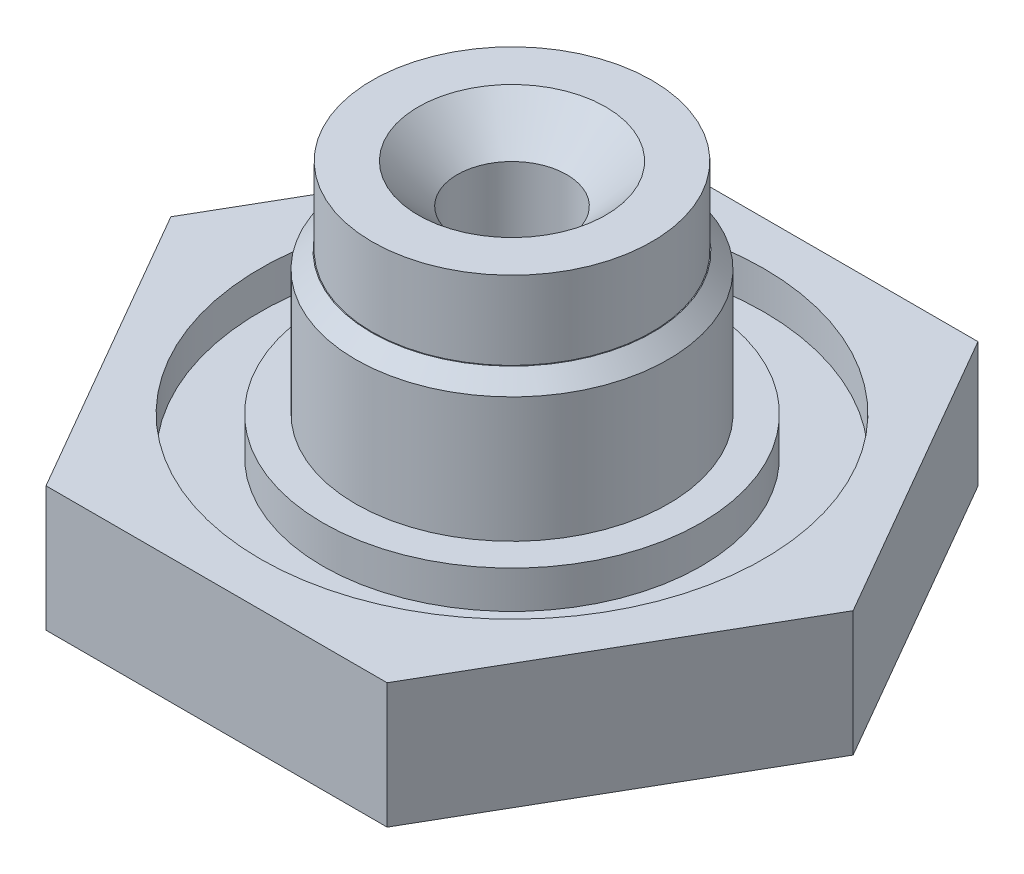
SolidWorks part; units mm, degrees
material "Acier allié inoxydable"
ref_plane "Front" through (0, 0, 0) normal (0, 0, 1) x (1, 0, 0)
ref_plane "Top" through (0, 0, 0) normal (0, 1, 0) x (1, 0, 0)
ref_plane "Right" through (0, 0, 0) normal (1, 0, 0) x (0, 0, -1)
sketch "Esquisse1" plane through (0, 0, 0) normal (0, 0, 1) x (1, 0, 0)
  line L0 (0, 0) -> (0, 16) construction
  line L1 (0.65, 0) -> (0.65, 1.5)
  line L2 (0.65, 1.5) -> (1.75, 2.6)
  line L3 (1.75, 2.6) -> (1.75, 14.75)
  line L4 (1.75, 14.75) -> (3, 16)
  line L5 (3, 16) -> (4.475, 16)
  line L7 (5, 9) -> (12.5, 9)
  line L8 (12.5, 9) -> (12.5, 5)
  line L10 (4.475, 16) -> (4.475, 13.5)
  line L11 (4.475, 13.5) -> (5, 13.5)
  line L12 (5, 13.5) -> (5, 9)
  line L13 (12.5, 5) -> (5.65, 5)
  line L14 (5.65, 5) -> (0.65, 0)
  dimension "D1" = 16
  dimension "D2" = 8.95
  dimension "D3" = 4
  dimension "D4" = 3.5
  dimension "D5" = 135
  dimension "D6" = 1.5
  dimension "D7" = 25
  dimension "D8" = 7
  dimension "D9" = 6
  dimension "D10" = 10
  dimension "D11" = 4.5
  dimension "D12" = 135
  dimension "D13" = 1.3
revolve "Révolution1" add sketch "Esquisse1" angle 360 about L0
chamfer "Chanfrein1" distance 0.5 angle 45 1 edges at (0, 13.5, -5)
sketch "Esquisse2" plane through (0, 9, 0) normal (0, 1, 0) x (1, 0, 0)
  line L0 (-10.9119, 0) -> (-5.456, 9.45)
  line L1 (-5.456, 9.45) -> (5.456, 9.45)
  line L2 (5.456, 9.45) -> (10.9119, 0)
  line L3 (10.9119, 0) -> (5.456, -9.45)
  line L4 (5.456, -9.45) -> (-5.456, -9.45)
  line L5 (-5.456, -9.45) -> (-10.9119, 0)
  line L6 (-8.1839, 4.725) -> (8.1839, -4.725) construction
  line L7 (8.1839, 4.725) -> (-8.1839, -4.725) construction
  circle A0 centre (0, 0) radius 12.5
  circle A1 centre (0, 0) radius 12.5 construction
  point P13 (0, 0)
  point P16 (0, 0)
  dimension "D1" = 120
  dimension "D2" = 120
  dimension "D3" = 18.9
extrude "Enlèv. mat.-Extru.1" cut sketch "Esquisse2" against normal through all
sketch "Esquisse3" plane through (0, 9, 0) normal (0, 1, 0) x (1, 0, 0)
  circle A0 centre (0, 0) radius 6.05
  circle A1 centre (0, 0) radius 8.05
  dimension "D1" = 12.1
  dimension "D2" = 2
extrude "Enlèv. mat.-Extru.2" cut sketch "Esquisse3" against normal blind 1.2
